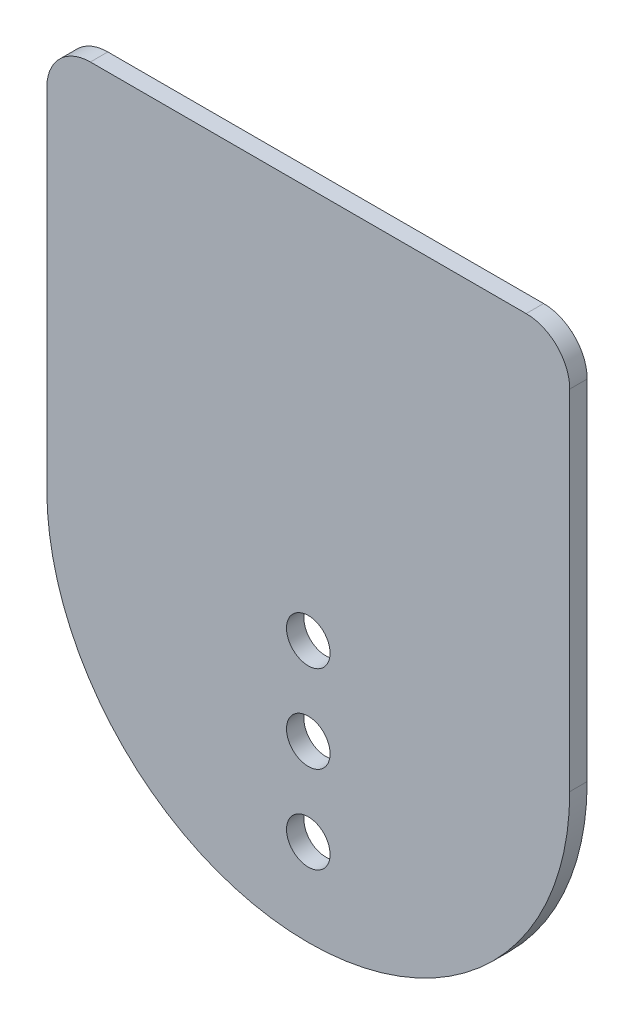
SolidWorks part; units mm, degrees
ref_plane "前视基准面" through (0, 0, 0) normal (0, 0, 1) x (1, 0, 0)
ref_plane "上视基准面" through (0, 0, 0) normal (0, 1, 0) x (1, 0, 0)
ref_plane "右视基准面" through (0, 0, 0) normal (1, 0, 0) x (0, 0, -1)
sketch "草图1" plane through (0, 0, 0) normal (0, 0, 1) x (1, 0, 0)
  line L0 (60, 52.2477) -> (60, -206.2786) construction
  line L1 (10, 0) -> (110, 0)
  line L2 (0, -10) -> (0, -90)
  line L4 (120, -10) -> (120, -90)
  line L5 (60, -130) -> (60, -110) construction
  arc A0 (0, -10) -> (10, 0) centre (10, -10) cw
  arc A1 (120, -10) -> (110, 0) centre (110, -10) ccw
  arc A2 (60, -150) -> (120, -90) centre (60, -90) ccw
  arc A3 (60, -150) -> (0, -90) centre (60, -90) cw
  circle A4 centre (60, -130) radius 5
  circle A5 centre (60, -110) radius 5
  circle A6 centre (60, -90) radius 5
  point P7 (0, 0)
  point P16 (60, 0)
  dimension "D1" = 120
  dimension "D2" = 10
  dimension "D3" = 60
  dimension "D5" = 10
  dimension "D4" = 150
  dimension "D7" = 20
  dimension "D6" = 3
extrude "凸台-拉伸1" add sketch "草图1" along normal mid plane 4
